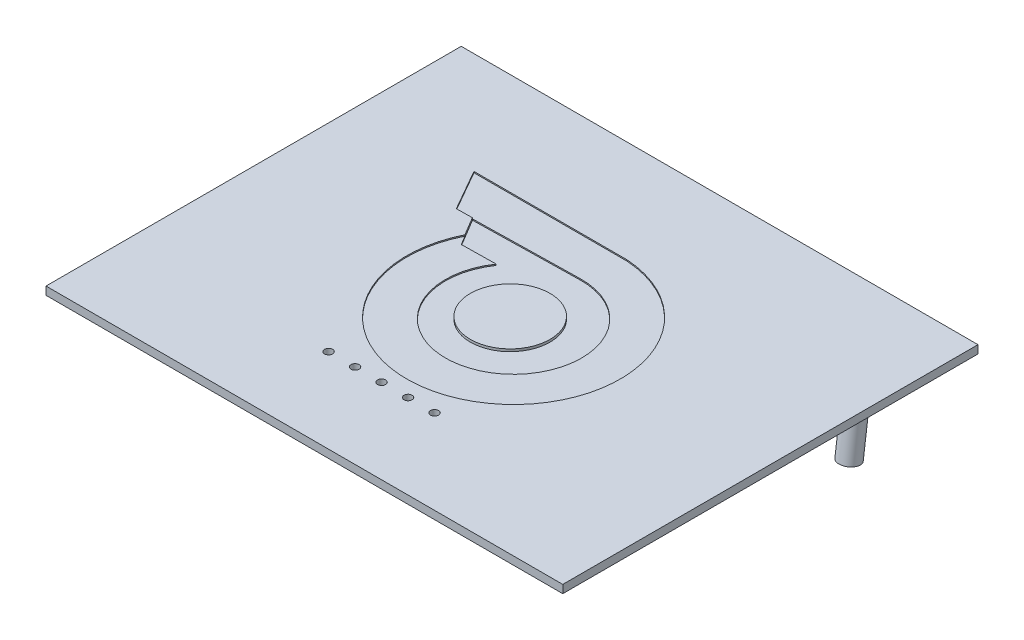
SolidWorks part; units mm, degrees
ref_plane "Front Plane" through (0, 0, 0) normal (0, 0, 1) x (1, 0, 0)
ref_plane "Top Plane" through (0, 0, 0) normal (0, 1, 0) x (1, 0, 0)
ref_plane "Right Plane" through (0, 0, 0) normal (1, 0, 0) x (0, 0, -1)
sketch "Sketch1" plane through (0, 0, 0) normal (0, 1, 0) x (1, 0, 0)
  line L1 (-64, -50.5) -> (64, -50.5)
  line L2 (-64, -50.5) -> (-64, 50.5)
  line L3 (-64, 50.5) -> (64, 50.5)
  line L4 (64, -50.5) -> (64, 50.5)
  line L5 (-64, -50.5) -> (64, 50.5) construction
  line L6 (-64, 50.5) -> (64, -50.5) construction
  point P0 (0, 0)
  dimension "D1" = 101
  dimension "D2" = 128
extrude "Boss-Extrude1" add sketch "Sketch1" along normal blind 2
sketch "Sketch2" plane through (0, 0, 0) normal (0, -1, 0) x (1, 0, 0)
  line L0 (-64, 49) -> (-62.9, 49) construction
  line L1 (-64, 50.5) -> (64, 50.5) construction
  line L2 (64, 49) -> (62.9, 49) construction
  line L3 (64, -50.5) -> (-64, -50.5) construction
  line L4 (62.9, 49) -> (61.7, 49)
  line L5 (62.9, 49) -> (62.9, -49)
  line L6 (62.9, -49) -> (61.7, -49)
  line L7 (61.7, 49) -> (61.7, -49)
  line L8 (-64, -51.87) -> (-64, 50.98) construction
  line L9 (-62.9, 49) -> (-61.7, 49)
  line L10 (-62.9, 49) -> (-62.9, -49)
  line L11 (-62.9, -49) -> (-61.7, -49)
  line L12 (-61.7, 49) -> (-61.7, -49)
  line L13 (-62.9, 49) -> (-62.9, 50.5) construction
  line L14 (64, 50.98) -> (64, -51.87) construction
  dimension "D1" = 1.1
  dimension "D2" = 1.1
  dimension "D3" = 1.2
  dimension "D4" = 1.2
  dimension "D5" = 1.5
  dimension "D6" = 1.5
  dimension "D7" = 1.5
  dimension "D8" = 1.5
extrude "Boss-Extrude2" add sketch "Sketch2" along normal blind 1
sketch "Sketch3" plane through (0, 0, 50.5) normal (0, 0, 1) x (1, 0, 0)
  line L1 (-64, 2) -> (64, 2)
  line L2 (-64, 2) -> (-64, 0)
  line L3 (-64, 0) -> (64, 0)
  line L4 (64, 2) -> (64, 0)
extrude "Boss-Extrude3" add sketch "Sketch3" along normal blind 0.48
sketch "Sketch4" plane through (0, 0, -50.5) normal (0, 0, -1) x (-1, 0, 0)
  line L1 (-64, 2) -> (64, 2)
  line L2 (-64, 2) -> (-64, 0)
  line L3 (-64, 0) -> (64, 0)
  line L4 (64, 2) -> (64, 0)
extrude "Boss-Extrude4" add sketch "Sketch4" along normal blind 1.37
sketch "Sketch5" plane through (0, -10.49, 1.3637) normal (0, 0.9917, -0.1289) x (1, 0, 0)
  circle A1 centre (-59.4789, 26.4337) radius 2.5 construction
  circle A3 centre (-59.4789, 26.4337) radius 2.5
  circle A5 centre (58.8211, 26.4337) radius 2.5 construction
  circle A7 centre (58.8211, 26.4337) radius 2.5
extrude "Boss-Extrude5" add sketch "Sketch5" along normal blind 13 from offset 2
hole_wizard "M3 Clearance Hole1" positions "Sketch7" profile "Sketch6" hole size "M3" standard "ANSI Metric"
sketch "Sketch7" plane through (0, -8.5067, 1.1059) normal (0, -0.9917, 0.1289) x (1, 0, 0)
  circle A1 centre (58.8211, -26.4337) radius 2.5 construction
  point P0 (58.8211, -26.4337)
  point P10 (58.8211, -26.4337)
sketch "Sketch6" plane through (58.8211, -11.9144, -25.1072) normal (1, 0, 0) x (0, -0.1289, -0.9917)
  line L0 (0, 0) -> (0, 10.7811)
  line L1 (0, 10.7811) -> (1.3, 10)
  line L2 (1.3, 10) -> (1.3, 0.2)
  line L3 (1.3, 0.2) -> (1.5, 0)
  line L5 (1.5, 0) -> (0, 0)
  line L6 (-1.3, 0.2) -> (-1.5, 0) construction
  line L10 (0, 10.7811) -> (-1.3, 10) construction
  line L11 (0, -6.35) -> (0, 107.95) construction
  dimension "Hole Dia." = 2.6
  dimension "Hole Depth" = 10
  dimension "Near C'Sink Dia." = 3
  dimension "Near C'Sink Angle" = 90
  dimension "Drill Angle" = 118
hole_wizard "M3 Clearance Hole2" positions "Sketch9" profile "Sketch8" hole size "M3" standard "ANSI Metric"
sketch "Sketch9" plane through (0, -8.5067, 1.1059) normal (0, -0.9917, 0.1289) x (1, 0, 0)
  circle A0 centre (-59.4789, -26.4337) radius 2.5 construction
  circle A1 centre (-59.4789, -26.4337) radius 2.5 construction
  point P0 (-59.4789, -26.4337)
sketch "Sketch8" plane through (-59.4789, -11.9144, -25.1072) normal (1, 0, 0) x (0, -0.1289, -0.9917)
  line L0 (0, 0) -> (0, 10.7811)
  line L1 (0, 10.7811) -> (1.3, 10)
  line L2 (1.3, 10) -> (1.3, 0.2)
  line L3 (1.3, 0.2) -> (1.5, 0)
  line L5 (1.5, 0) -> (0, 0)
  line L6 (-1.3, 0.2) -> (-1.5, 0) construction
  line L10 (0, 10.7811) -> (-1.3, 10) construction
  line L11 (0, -6.35) -> (0, 107.95) construction
  dimension "Hole Dia." = 2.6
  dimension "Hole Depth" = 10
  dimension "Near C'Sink Dia." = 3
  dimension "Near C'Sink Angle" = 90
  dimension "Drill Angle" = 118
ref_plane "Plane1" through (-21.0589, -2.7915, 45.8445) normal (1, 0, 0) x (0, 0, -1)
ref_plane "Plane2" through (17.4411, -2.7928, 45.8346) normal (0, -0.9917, 0.1289) x (-1, 0, 0)
sketch "Sketch13" plane through (0, -8.9034, 1.1574) normal (0, 0.9917, -0.1289) x (1, 0, 0)
  line L0 (-21.0589, -45.1021) -> (17.4411, -45.1021) construction
  line L1 (-21.0589, -45.1021) -> (17.4411, -45.1021)
sketch "Sketch14" plane through (0, 0, 0) normal (0, -1, 0) x (1, 0, 0)
  line L0 (-21.0589, 35.257) -> (-21.0589, 56.432) construction
  line L2 (17.4411, 31.0543) -> (17.4411, 29.0543) construction
  line L3 (17.4411, 29.0543) -> (-21.0589, 29.0543) construction
  line L4 (-21.0589, 31.0543) -> (-21.0589, 29.0543) construction
  line L7 (-15.3761, 31.0543) -> (-15.3761, 29.0543) construction
  line L8 (-15.3761, 29.0543) -> (-14.4954, 29.0543) construction
  line L9 (-14.4954, 31.0543) -> (-14.4954, 29.0543) construction
  line L10 (-8.8127, 31.0543) -> (-8.8127, 29.0543) construction
  line L11 (-8.8127, 29.0543) -> (-7.9319, 29.0543) construction
  line L12 (-7.9319, 31.0543) -> (-7.9319, 29.0543) construction
  line L14 (10.8777, 31.0543) -> (10.8777, 29.0543) construction
  line L15 (10.8777, 29.0543) -> (11.7584, 29.0543) construction
  line L16 (11.7584, 31.0543) -> (11.7584, 29.0543) construction
  line L18 (4.3142, 31.0543) -> (4.3142, 29.0543) construction
  line L19 (4.3142, 29.0543) -> (5.195, 29.0543) construction
  line L20 (5.195, 31.0543) -> (5.195, 29.0543) construction
  line L21 (-21.0589, 31.0543) -> (-15.3761, 31.0543) construction
  line L22 (-15.3761, 31.0543) -> (-14.4954, 31.0543) construction
  line L23 (-14.4954, 31.0543) -> (-8.8127, 31.0543) construction
  line L24 (-7.9319, 31.0543) -> (-8.8127, 31.0543) construction
  line L25 (-7.9319, 31.0543) -> (-2.2492, 31.0543) construction
  line L26 (5.195, 31.0543) -> (4.3142, 31.0543) construction
  line L27 (5.195, 31.0543) -> (10.8777, 31.0543) construction
  line L28 (10.8777, 31.0543) -> (11.7584, 31.0543) construction
  line L29 (11.7584, 31.0543) -> (17.4411, 31.0543) construction
  line L30 (-15.3761, 31.0543) -> (-14.4954, 29.0543) construction
  line L31 (-8.8127, 31.0543) -> (-7.9319, 29.0543) construction
  line L32 (4.3142, 31.0543) -> (5.195, 29.0543) construction
  line L33 (10.8777, 31.0543) -> (11.7584, 29.0543) construction
  line L34 (-21.0589, 30.0543) -> (17.4411, 30.0543) construction
  line L35 (-2.2492, 31.0543) -> (-2.2492, 29.0543) construction
  line L36 (-1.3685, 31.0543) -> (-1.3685, 29.0543) construction
  line L37 (-1.3685, 31.0543) -> (-2.2492, 31.0543) construction
  line L38 (-2.2492, 31.0543) -> (-1.3685, 29.0543) construction
  line L39 (-1.3685, 31.0543) -> (4.3142, 31.0543) construction
  circle A1 centre (-8.3723, 30.0543) radius 1
  circle A2 centre (4.7546, 30.0543) radius 1
  circle A3 centre (11.3181, 30.0543) radius 1
  circle A4 centre (-14.9358, 30.0543) radius 1
  circle A5 centre (-1.8089, 30.0543) radius 1
  point P25 (-15.3761, 31.0543)
  dimension "D1" = 2
  dimension "D2" = 38.5
sketch "Sketch15" plane through (0, 0, 0) normal (0, -1, 0) x (1, 0, 0)
  line L0 (-16.4315, 32.0543) -> (-14.9358, 30.0543) construction
  line L1 (-16.4315, 32.0543) -> (14.7611, 32.0543)
  line L3 (-16.4315, 28.0543) -> (14.7611, 28.0543)
  line L5 (14.7611, 28.0543) -> (19.7611, 28.0543)
  line L7 (14.7611, 32.0543) -> (19.7611, 32.0543)
  line L8 (19.7611, 28.0543) -> (19.7611, 32.0543)
  line L9 (-16.4315, 32.0543) -> (-21.4315, 32.0543)
  line L11 (-16.4315, 28.0543) -> (-21.4315, 28.0543)
  line L12 (-21.4315, 32.0543) -> (-21.4315, 28.0543)
  line L13 (-14.9358, 30.0543) -> (-16.4315, 28.0543) construction
  line L14 (-16.4315, 32.0543) -> (-16.4315, 28.0543) construction
  line L15 (-21.4315, 30.0543) -> (19.7611, 30.0543) construction
  circle A0 centre (11.3181, 30.0543) radius 1 construction
  circle A1 centre (4.7546, 30.0543) radius 1 construction
  circle A2 centre (-8.3723, 30.0543) radius 1 construction
  circle A3 centre (-14.9358, 30.0543) radius 1 construction
  circle A4 centre (11.3181, 30.0543) radius 1 construction
  circle A5 centre (4.7546, 30.0543) radius 1 construction
  circle A6 centre (-8.3723, 30.0543) radius 1 construction
  circle A7 centre (-14.9358, 30.0543) radius 1 construction
  dimension "D1" = 5
  dimension "D2" = 5
  dimension "D3" = 4
extrude "Cut-Extrude1" cut sketch "Sketch14" against normal blind 5
extrude "Cut-Extrude2" cut sketch "Sketch15" against normal blind 0.4
sketch "Sketch28" plane through (0, 2, 0) normal (0, 1, 0) x (1, 0, 0)
  line L0 (-105.9112, 39.4438) -> (44.0888, 39.4438) construction
  line L13 (-35.5896, 26.6111) -> (2.3582, 26.6111)
  line L14 (-35.5896, 26.6111) -> (-29.7648, 16.4235)
  line L15 (-29.7648, 16.4235) -> (-20.1685, 16.5748)
  line L16 (-25.8891, 16.5492) -> (-21.7753, 9.6578)
  line L17 (-21.7753, 9.6578) -> (-13.2552, 9.7921)
  line L18 (-25.8891, 16.5492) -> (0.2164, 17.0688)
  circle A7 centre (0, 0) radius 9.8716
  arc A8 (-20.1685, 16.5748) -> (2.3582, 26.6111) centre (0.6217, 0.2096) ccw
  arc A9 (-13.2552, 9.7921) -> (0.2164, 17.0688) centre (0.6217, 0.2096) ccw
sketch "Sketch31" plane through (0, 2, 0) normal (0, 1, 0) x (1, 0, 0)
  line L0 (-35.5896, 26.6111) -> (2.3582, 26.6111) construction
  line L1 (-35.5896, 26.6111) -> (-29.7648, 16.4235) construction
  line L2 (-29.7648, 16.4235) -> (-20.1685, 16.5748) construction
  line L3 (-35.5896, 26.6111) -> (2.3582, 26.6111)
  line L4 (-35.5896, 26.6111) -> (-29.7648, 16.4235)
  line L5 (-29.7648, 16.4235) -> (-20.1685, 16.5748)
  arc A0 (-20.1685, 16.5748) -> (2.3582, 26.6111) centre (0.6217, 0.2096) ccw construction
  arc A1 (-20.1685, 16.5748) -> (2.3582, 26.6111) centre (0.6217, 0.2096) ccw
sketch "Sketch29" plane through (0, 2, 0) normal (0, 1, 0) x (1, 0, 0)
  line L0 (-25.8891, 16.5492) -> (0.2164, 17.0688) construction
  line L1 (-25.8891, 16.5492) -> (-21.7753, 9.6578) construction
  line L2 (-21.7753, 9.6578) -> (-13.2552, 9.7921) construction
  line L3 (-25.8891, 16.5492) -> (0.2164, 17.0688)
  line L4 (-25.8891, 16.5492) -> (-21.7753, 9.6578)
  line L5 (-21.7753, 9.6578) -> (-13.2552, 9.7921)
  arc A0 (-13.2552, 9.7921) -> (0.2164, 17.0688) centre (0.6217, 0.2096) ccw construction
  arc A1 (-13.2552, 9.7921) -> (0.2164, 17.0688) centre (0.6217, 0.2096) ccw
sketch "Sketch30" plane through (0, 2, 0) normal (0, 1, 0) x (1, 0, 0)
  circle A0 centre (0, 0) radius 9.8716 construction
  circle A1 centre (0, 0) radius 9.8716
extrude "Cut-Extrude4" cut sketch "Sketch31" against normal blind 0.3
extrude "Cut-Extrude5" cut sketch "Sketch29" against normal blind 0.6
extrude "Boss-Extrude13" add sketch "Sketch30" against normal blind 0.6 separate body
